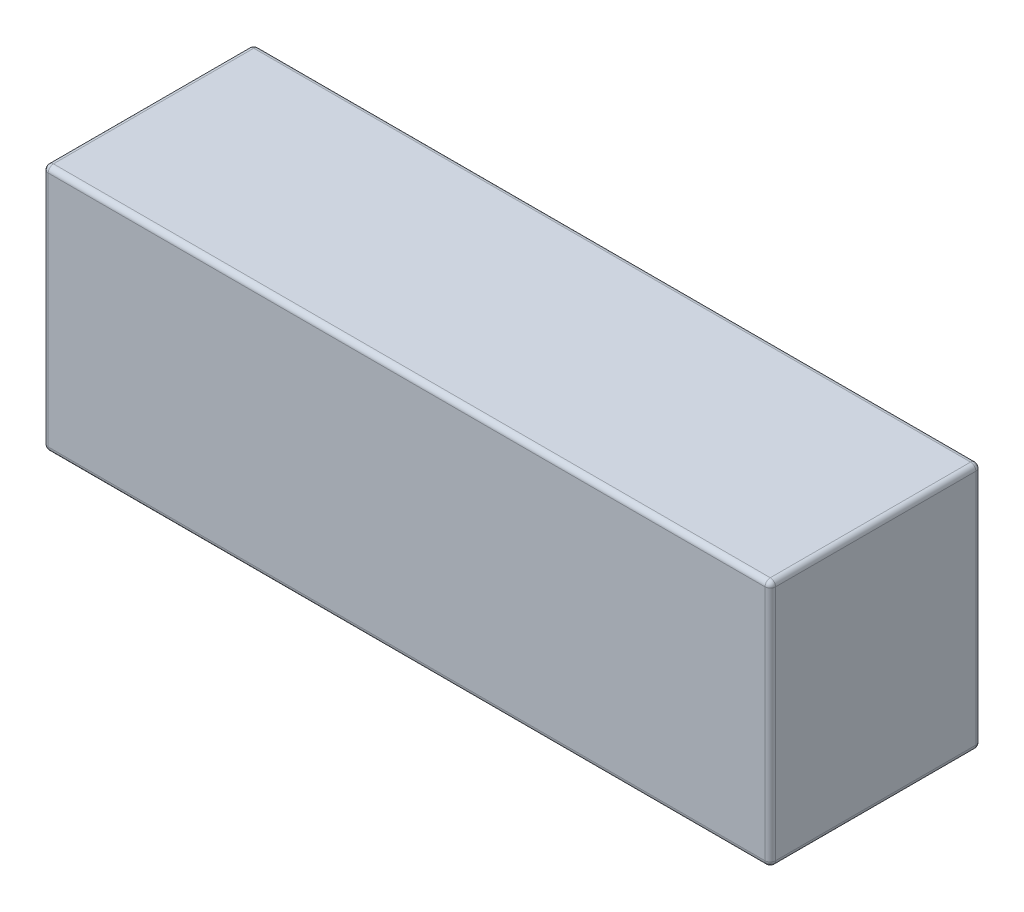
SolidWorks part; units mm, degrees
ref_plane "Front Plane" through (0, 0, 0) normal (0, 0, 1) x (1, 0, 0)
ref_plane "Top Plane" through (0, 0, 0) normal (0, 1, 0) x (1, 0, 0)
ref_plane "Right Plane" through (0, 0, 0) normal (1, 0, 0) x (0, 0, -1)
sketch "Sketch1" plane through (0, 0, 0) normal (0, 0, 1) x (1, 0, 0)
  line L1 (-69, 23.5) -> (69, 23.5)
  line L2 (-69, 23.5) -> (-69, -23.5)
  line L3 (-69, -23.5) -> (69, -23.5)
  line L4 (69, 23.5) -> (69, -23.5)
  line L5 (-69, 23.5) -> (69, -23.5) construction
  line L6 (-69, -23.5) -> (69, 23.5) construction
  point P0 (0, 0)
  dimension "D1" = 138
  dimension "D2" = 47
extrude "Boss-Extrude1" add sketch "Sketch1" along normal mid plane 40
fillet "Fillet1" radius 1 12 edges at (-69, -23.5, 0) (0, -23.5, 20) (-69, 0, 20) (0, 23.5, 20) (0, 23.5, -20) (-69, 23.5, 0) (-69, 0, -20) (0, -23.5, -20) (69, -23.5, 0) (69, 0, -20) (69, 23.5, 0) (69, 0, 20)
